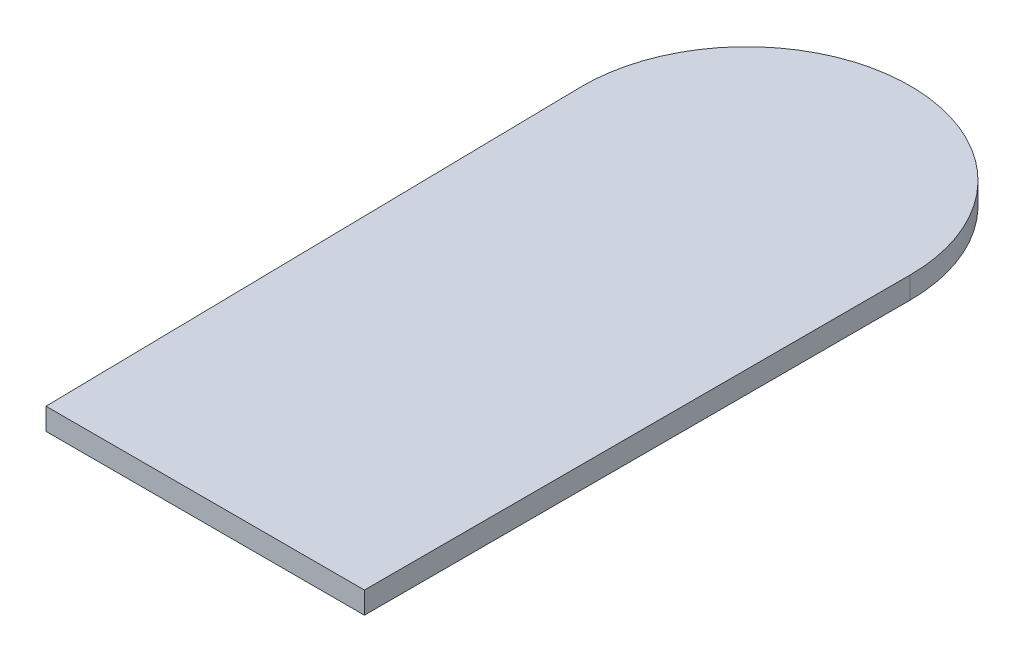
SolidWorks part; units mm, degrees
ref_plane "Front Plane" through (0, 0, 0) normal (0, 0, 1) x (1, 0, 0)
ref_plane "Top Plane" through (0, 0, 0) normal (0, 1, 0) x (1, 0, 0)
ref_plane "Right Plane" through (0, 0, 0) normal (1, 0, 0) x (0, 0, -1)
sketch "Sketch1" plane through (0, 0, 0) normal (0, 1, 0) x (1, 0, 0)
  line L0 (-22.4969, -0.3747) -> (-21.254, -75)
  line L1 (-21.254, -75) -> (22.5, -75)
  line L2 (22.5, -75) -> (22.5, 0)
  arc A0 (-22.4969, -0.3747) -> (22.5, 0) centre (0, 0) cw
  dimension "D1" = 22.5
  dimension "D2" = 75
extrude "Boss-Extrude1" add sketch "Sketch1" along normal blind 3 contours A0 L2 L1 L0
